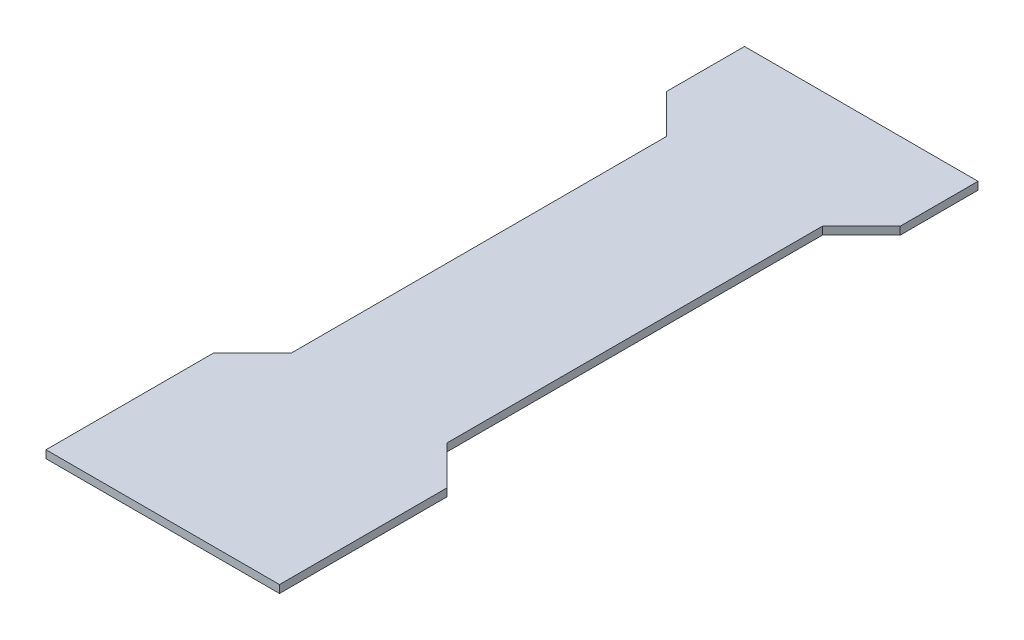
SolidWorks part; units mm, degrees
ref_plane "前视基准面" through (0, 0, 0) normal (0, 0, 1) x (1, 0, 0)
ref_plane "上视基准面" through (0, 0, 0) normal (0, 1, 0) x (1, 0, 0)
ref_plane "右视基准面" through (0, 0, 0) normal (1, 0, 0) x (0, 0, -1)
sketch "草图1" plane through (0, 0, 0) normal (0, 1, 0) x (1, 0, 0)
  line L26 (30, 159.5) -> (30, 179.5)
  line L33 (30, 43) -> (20, 53)
  line L34 (20, 139.5) -> (20, 53)
  line L35 (30, 159.5) -> (20, 149.5)
  line L36 (20, 149.5) -> (20, 139.5)
  line L37 (-30, 179.5) -> (30, 179.5)
  line L38 (-20, 149.5) -> (-20, 139.5)
  line L39 (-30, 159.5) -> (-20, 149.5)
  line L40 (-20, 139.5) -> (-20, 53)
  line L41 (-30, 43) -> (-20, 53)
  line L42 (-30, 159.5) -> (-30, 179.5)
  line L43 (30, 43) -> (30, 0)
  line L44 (30, 0) -> (0, 0)
  line L45 (0, 0) -> (-30, 0)
  line L46 (-30, 0) -> (-30, 43)
  point P27 (0, 320)
extrude "凸台-拉伸1" add sketch "草图1" along normal blind 2
